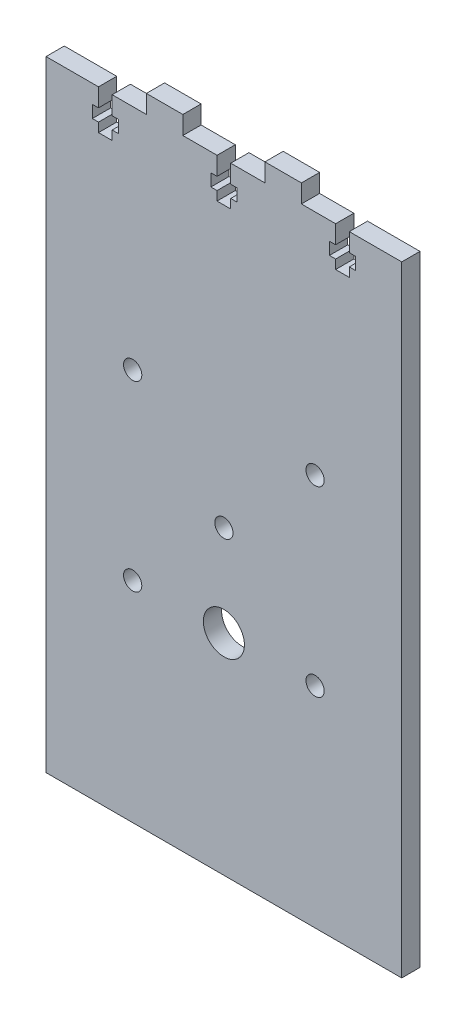
SolidWorks part; units mm, degrees
ref_plane "前视基准面" through (0, 0, 0) normal (0, 0, 1) x (1, 0, 0)
ref_plane "上视基准面" through (0, 0, 0) normal (0, 1, 0) x (1, 0, 0)
ref_plane "右视基准面" through (0, 0, 0) normal (1, 0, 0) x (0, 0, -1)
sketch "草图1" plane through (0, 0, 0) normal (0, 0, 1) x (1, 0, 0)
  line L0 (0, 20) -> (39, 20) construction
  line L2 (-39, 90) -> (-39, -46)
  line L3 (-39, -46) -> (39, -46)
  line L4 (39, 90) -> (39, -46)
  line L5 (0, 20) -> (-39, 20) construction
  line L6 (39, 90) -> (27.5, 90)
  line L7 (-27.5, 90) -> (-39, 90)
  line L59 (-39, 22) -> (-46.9885, 22) construction
  line L60 (-13, 94) -> (-13, 82.6313) construction
  line L61 (-26, 90) -> (-27.5, 90) construction
  line L62 (-26, 90) -> (-26, 81.3) construction
  line L63 (26, 90) -> (26, 81.3) construction
  line L64 (26, 90) -> (27.5, 90) construction
  line L65 (13, 94) -> (13, 82.6313) construction
  line L66 (0, 90) -> (-1.5, 90) construction
  line L67 (0, 90) -> (0, 81.3) construction
  line L68 (-9, 90) -> (-1.5, 90)
  line L69 (-9, 90) -> (-9, 94)
  line L70 (-9, 94) -> (-17, 94)
  line L71 (-17, 94) -> (-17, 90)
  line L72 (-24.5, 83.3) -> (-24.5, 81.3)
  line L73 (-23.15, 83.3) -> (-24.5, 83.3)
  line L74 (-24.5, 86) -> (-23.15, 86)
  line L75 (-23.15, 86) -> (-23.15, 83.3)
  line L76 (-24.5, 90) -> (-24.5, 86)
  line L77 (-27.5, 81.3) -> (-24.5, 81.3)
  line L78 (-27.5, 83.3) -> (-27.5, 81.3)
  line L79 (-28.85, 83.3) -> (-27.5, 83.3)
  line L80 (-28.85, 86) -> (-28.85, 83.3)
  line L81 (-27.5, 86) -> (-28.85, 86)
  line L82 (-27.5, 90) -> (-27.5, 86)
  line L83 (-17, 90) -> (-24.5, 90)
  line L84 (17, 90) -> (24.5, 90)
  line L85 (1.5, 90) -> (9, 90)
  line L86 (27.5, 90) -> (27.5, 86)
  line L87 (27.5, 86) -> (28.85, 86)
  line L88 (28.85, 86) -> (28.85, 83.3)
  line L89 (28.85, 83.3) -> (27.5, 83.3)
  line L90 (27.5, 83.3) -> (27.5, 81.3)
  line L91 (27.5, 81.3) -> (24.5, 81.3)
  line L92 (24.5, 90) -> (24.5, 86)
  line L93 (23.15, 86) -> (23.15, 83.3)
  line L94 (24.5, 86) -> (23.15, 86)
  line L95 (23.15, 83.3) -> (24.5, 83.3)
  line L96 (24.5, 83.3) -> (24.5, 81.3)
  line L97 (17, 94) -> (17, 90)
  line L98 (9, 94) -> (17, 94)
  line L99 (9, 90) -> (9, 94)
  line L100 (1.5, 83.3) -> (1.5, 81.3)
  line L101 (2.85, 83.3) -> (1.5, 83.3)
  line L102 (1.5, 86) -> (2.85, 86)
  line L103 (2.85, 86) -> (2.85, 83.3)
  line L104 (1.5, 90) -> (1.5, 86)
  line L105 (-1.5, 81.3) -> (1.5, 81.3)
  line L106 (-1.5, 83.3) -> (-1.5, 81.3)
  line L107 (-2.85, 83.3) -> (-1.5, 83.3)
  line L108 (-2.85, 86) -> (-2.85, 83.3)
  line L109 (-1.5, 86) -> (-2.85, 86)
  line L110 (-1.5, 90) -> (-1.5, 86)
  line L112 (-24.5, 90) -> (-17, 90)
  line L113 (-1.5, 90) -> (-9, 90)
  line L114 (1.5, 90) -> (9, 90)
  line L115 (17, 90) -> (24.5, 90)
  circle A0 centre (0, 0) radius 4.5
  circle A2 centre (20, 0) radius 2
  circle A3 centre (0, 20) radius 2
  circle A8 centre (-20, 40) radius 2
  circle A9 centre (-20, 0) radius 2
  circle A10 centre (20, 40) radius 2
  dimension "D1" = 9
  dimension "D4" = 4
  dimension "D2" = 20
  dimension "D3" = 20
  dimension "D6" = 39
  dimension "D8" = 40
  dimension "D9" = 46
  dimension "D5" = 20
extrude "凸台-拉伸1" add sketch "草图1" along normal blind 4
sketch "草图2" plane through (0, 90, 0) normal (0, 1, 0) x (1, 0, 0)
  line L0 (1.5, -2) -> (-1.5, -2)
  line L1 (1.5, -4) -> (1.5, 0) construction
  line L2 (-1.5, -4) -> (-1.5, 0) construction
  circle A0 centre (0, -2) radius 1.5
